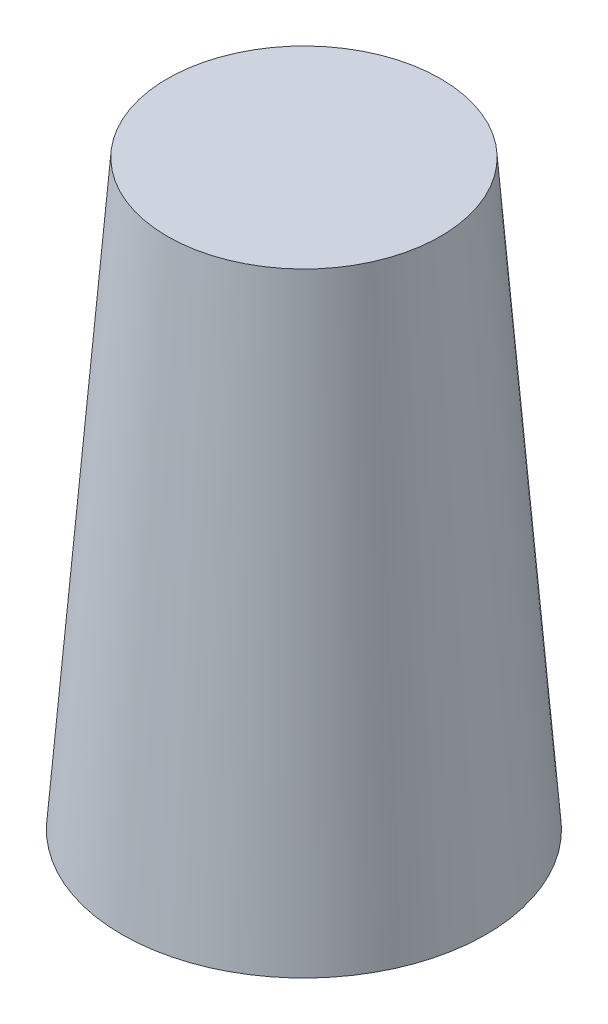
SolidWorks part; units mm, degrees
material "PP copolymère"
ref_plane "Plan de face" through (0, 0, 0) normal (0, 0, 1) x (1, 0, 0)
ref_plane "Plan de dessus" through (0, 0, 0) normal (0, 1, 0) x (1, 0, 0)
ref_plane "Plan de droite" through (0, 0, 0) normal (1, 0, 0) x (0, 0, -1)
sketch "Esquisse1" plane through (0, 0, 0) normal (0, 0, 1) x (1, 0, 0)
  line L0 (0, 115) -> (27, 115)
  line L1 (27, 115) -> (36, 0)
  line L2 (0, 115) -> (0, 0) construction
  line L3 (0, 113.5) -> (25.6128, 113.5)
  line L4 (25.6128, 113.5) -> (34.4954, 0)
  line L5 (0, 115) -> (0, 113.5)
  line L7 (36, 0) -> (34.4954, 0)
  line L8 (25.6128, 113.5) -> (34.5046, -0.117) construction
  point P2 (0, 460)
  dimension "D1" = 115
  dimension "D2" = 54
  dimension "D3" = 72
  dimension "D5" = 460
  dimension "D6" = 4.475
  dimension "D4" = 1.5
revolve "Révolution1" add sketch "Esquisse1" angle 360 about L2
